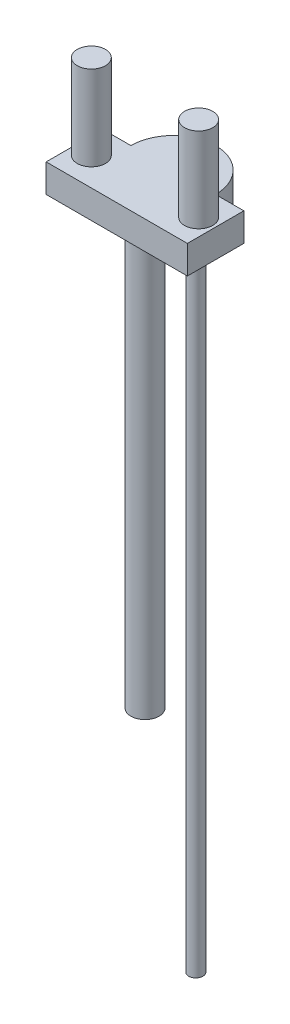
SolidWorks part; units mm, degrees
ref_plane "Front Plane" through (0, 0, 0) normal (0, 0, 1) x (1, 0, 0)
ref_plane "Top Plane" through (0, 0, 0) normal (0, 1, 0) x (1, 0, 0)
ref_plane "Right Plane" through (0, 0, 0) normal (1, 0, 0) x (0, 0, -1)
sketch "Sketch1" plane through (0, 0, 0) normal (0, 1, 0) x (1, 0, 0)
  circle A0 centre (0, 0) radius 5
  dimension "D1" = 10
extrude "Boss-Extrude1" add sketch "Sketch1" along normal blind 150
sketch "Sketch2" plane through (0, 150, 0) normal (0, 1, 0) x (1, 0, 0)
  line L1 (-25, 10) -> (25, 10)
  line L2 (-25, 10) -> (-25, -10)
  line L3 (-25, -10) -> (25, -10)
  line L4 (25, 10) -> (25, -10)
  line L5 (-25, 10) -> (25, -10) construction
  line L6 (-25, -10) -> (25, 10) construction
  point P0 (0, 0)
  dimension "D1" = 20
  dimension "D2" = 50
extrude "Boss-Extrude2" add sketch "Sketch2" along normal blind 10
sketch "Sketch3" plane through (0, 160, 0) normal (0, 1, 0) x (1, 0, 0)
  line L0 (25, -10) -> (25, 10) construction
  line L1 (-25, 10) -> (-25, -10) construction
  circle A0 centre (-19, 0) radius 5
  circle A1 centre (19, 0) radius 5
  dimension "D1" = 10
  dimension "D2" = 10
  dimension "D3" = 6
  dimension "D4" = 6
extrude "Boss-Extrude3" add sketch "Sketch3" along normal blind 30
sketch "Sketch4" plane through (0, 160, 0) normal (0, 1, 0) x (1, 0, 0)
  line L0 (25, 10) -> (-25, 10) construction
  line L1 (-15, 10) -> (15, 10)
  arc A0 (15, 10) -> (-15, 10) centre (0, 10) ccw
  dimension "D1" = 30
extrude "Boss-Extrude4" add sketch "Sketch4" against normal blind 10
sketch "Sketch5" plane through (0, 160, 0) normal (0, 1, 0) x (1, 0, 0)
  circle A0 centre (0, 18) radius 2.5
  dimension "D1" = 5
  dimension "D2" = 18
extrude "Boss-Extrude5" add sketch "Sketch5" against normal blind 250
